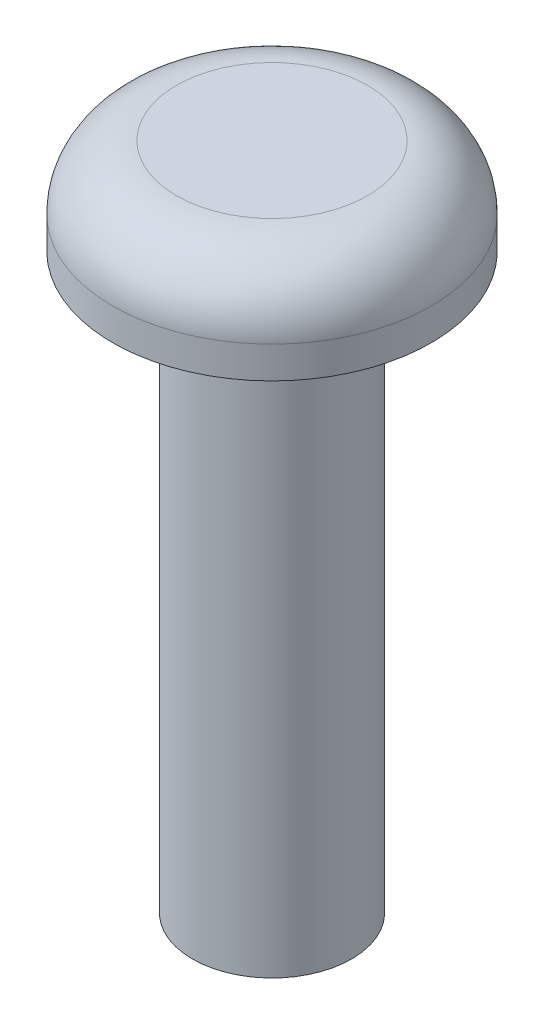
SolidWorks part; units mm, degrees
ref_plane "Front Plane" through (0, 0, 0) normal (0, 0, 1) x (1, 0, 0)
ref_plane "Top Plane" through (0, 0, 0) normal (0, 1, 0) x (1, 0, 0)
ref_plane "Right Plane" through (0, 0, 0) normal (1, 0, 0) x (0, 0, -1)
sketch "Sketch1" plane through (0, 0, 0) normal (0, 1, 0) x (1, 0, 0)
  circle A0 centre (0, 0) radius 0.635
  dimension "D1" = 1.27
extrude "Boss-Extrude1" add sketch "Sketch1" along normal blind 4.572
sketch "Sketch2" plane through (0, 4.572, 0) normal (0, 1, 0) x (1, 0, 0)
  circle A0 centre (0, 0) radius 1.27
  dimension "D1" = 2.54
extrude "Boss-Extrude2" add sketch "Sketch2" along normal blind 0.762
fillet "Fillet1" radius 0.508 1 edges at (0, 5.334, 1.27)
equation "\"revolve_angle\"=45"
equation "\"part_width\"=0.03"
equation "\"notch_offset\"=0.1"
equation "\"screw_diam\"=0.05"
equation "\"D1@Sketch1\"=\"screw_diam\""
equation "\"D1@Boss-Extrude1\"=\"part_width\"*6"
equation "\"D1@Sketch2\"=\"screw_diam\"*2"
equation "\"D1@Boss-Extrude2\"=\"part_width\""
